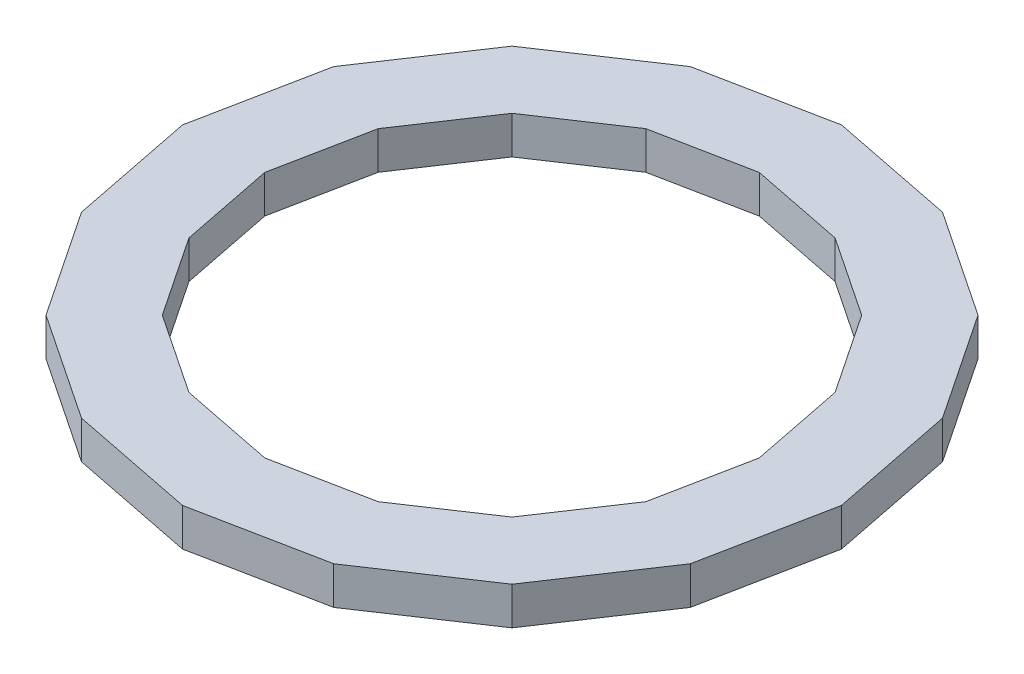
SolidWorks part; units mm, degrees
ref_plane "Front Plane" through (0, 0, 0) normal (0, 0, 1) x (1, 0, 0)
ref_plane "Top Plane" through (0, 0, 0) normal (0, 1, 0) x (1, 0, 0)
ref_plane "Right Plane" through (0, 0, 0) normal (1, 0, 0) x (0, 0, -1)
sketch "Sketch1" plane through (0, 0, 0) normal (0, 1, 0) x (1, 0, 0)
  line L1 (124.5638, 0) -> (115.082, 47.6685)
  line L2 (115.082, 47.6685) -> (88.0799, 88.0799)
  line L3 (88.0799, 88.0799) -> (47.6685, 115.082)
  line L4 (47.6685, 115.082) -> (0, 124.5638)
  line L5 (0, 124.5638) -> (-47.6685, 115.082)
  line L6 (-47.6685, 115.082) -> (-88.0799, 88.0799)
  line L7 (-88.0799, 88.0799) -> (-115.082, 47.6685)
  line L8 (-115.082, 47.6685) -> (-124.5638, 0)
  line L9 (-124.5638, 0) -> (-115.082, -47.6685)
  line L10 (-115.082, -47.6685) -> (-88.0799, -88.0799)
  line L11 (-88.0799, -88.0799) -> (-47.6685, -115.082)
  line L12 (-47.6685, -115.082) -> (0, -124.5638)
  line L13 (0, -124.5638) -> (47.6685, -115.082)
  line L14 (47.6685, -115.082) -> (88.0799, -88.0799)
  line L15 (88.0799, -88.0799) -> (115.082, -47.6685)
  line L16 (115.082, -47.6685) -> (124.5638, 0)
  line L17 (166, 0) -> (153.364, 63.5255)
  line L18 (153.364, 63.5255) -> (117.3797, 117.3797)
  line L19 (117.3797, 117.3797) -> (63.5255, 153.364)
  line L20 (63.5255, 153.364) -> (0, 166)
  line L21 (0, 166) -> (-63.5255, 153.364)
  line L22 (-63.5255, 153.364) -> (-117.3797, 117.3797)
  line L23 (-117.3797, 117.3797) -> (-153.364, 63.5255)
  line L24 (-153.364, 63.5255) -> (-166, 0)
  line L25 (-166, 0) -> (-153.364, -63.5255)
  line L26 (-153.364, -63.5255) -> (-117.3797, -117.3797)
  line L27 (-117.3797, -117.3797) -> (-63.5255, -153.364)
  line L28 (-63.5255, -153.364) -> (0, -166)
  line L29 (0, -166) -> (63.5255, -153.364)
  line L30 (63.5255, -153.364) -> (117.3797, -117.3797)
  line L31 (117.3797, -117.3797) -> (153.364, -63.5255)
  line L32 (153.364, -63.5255) -> (166, 0)
  circle A0 centre (0, 0) radius 122.1704 construction
  circle A1 centre (0, 0) radius 162.8104 construction
  dimension "D1" = 40.64
  dimension "D2" = 64.77
extrude "Boss-Extrude1" add sketch "Sketch1" along normal blind 19.05
